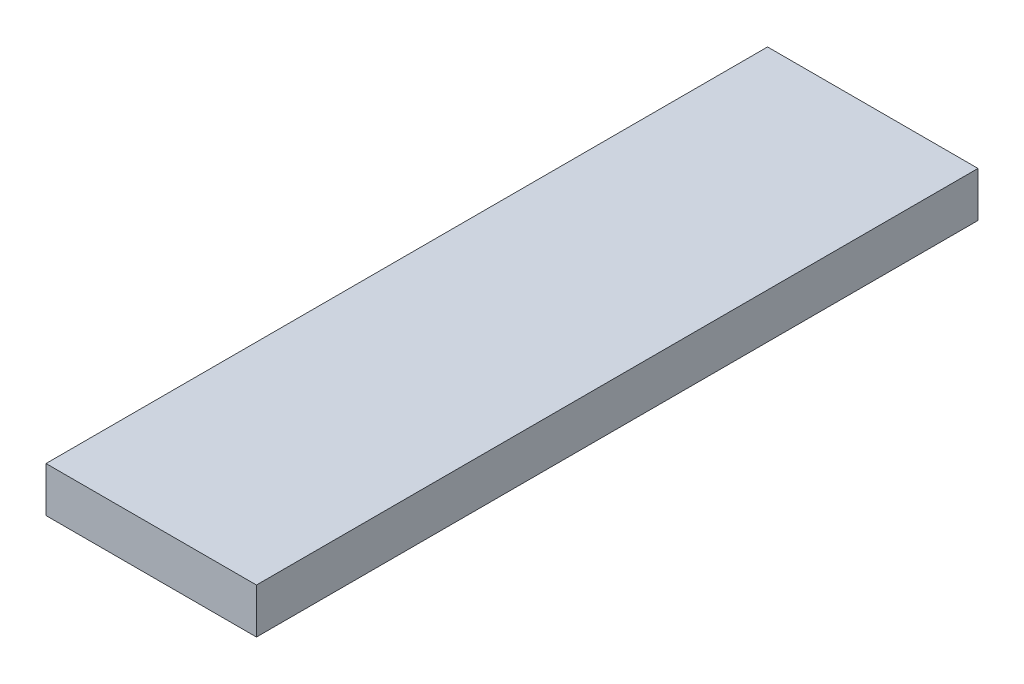
SolidWorks part; units mm, degrees
ref_plane "Front Plane" through (0, 0, 0) normal (0, 0, 1) x (1, 0, 0)
ref_plane "Top Plane" through (0, 0, 0) normal (0, 1, 0) x (1, 0, 0)
ref_plane "Right Plane" through (0, 0, 0) normal (1, 0, 0) x (0, 0, -1)
sketch "Sketch2" plane through (0, 0, 0) normal (0, 0, 1) x (1, 0, 0)
  line L1 (-44.45, 9.525) -> (44.45, 9.525)
  line L2 (-44.45, 9.525) -> (-44.45, -9.525)
  line L3 (-44.45, -9.525) -> (44.45, -9.525)
  line L4 (44.45, 9.525) -> (44.45, -9.525)
  line L5 (-44.45, 9.525) -> (44.45, -9.525) construction
  line L6 (-44.45, -9.525) -> (44.45, 9.525) construction
  point P0 (0, 0)
  dimension "D1" = 19.05
  dimension "D2" = 88.9
extrude "Boss-Extrude1" add sketch "Sketch2" along normal mid plane 304.8
